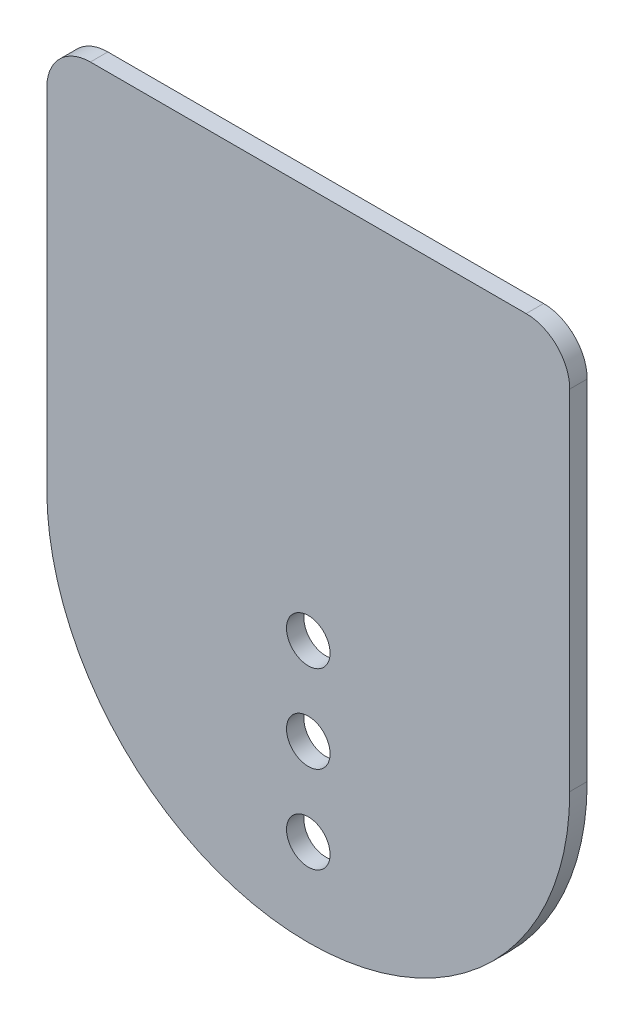
SolidWorks part; units mm, degrees
ref_plane "前视基准面" through (0, 0, 0) normal (0, 0, 1) x (1, 0, 0)
ref_plane "上视基准面" through (0, 0, 0) normal (0, 1, 0) x (1, 0, 0)
ref_plane "右视基准面" through (0, 0, 0) normal (1, 0, 0) x (0, 0, -1)
sketch "草图1" plane through (0, 0, 0) normal (0, 0, 1) x (1, 0, 0)
  line L0 (60, 52.2477) -> (60, -206.2786) construction
  line L1 (10, 0) -> (110, 0)
  line L2 (0, -10) -> (0, -90)
  line L4 (120, -10) -> (120, -90)
  line L5 (60, -130) -> (60, -110) construction
  arc A0 (0, -10) -> (10, 0) centre (10, -10) cw
  arc A1 (120, -10) -> (110, 0) centre (110, -10) ccw
  arc A2 (60, -150) -> (120, -90) centre (60, -90) ccw
  arc A3 (60, -150) -> (0, -90) centre (60, -90) cw
  circle A4 centre (60, -130) radius 5
  circle A5 centre (60, -110) radius 5
  circle A6 centre (60, -90) radius 5
  point P7 (0, 0)
  point P12 (0, 0)
  point P16 (60, 0)
  dimension "D1" = 120
  dimension "D2" = 10
  dimension "D3" = 60
  dimension "D5" = 10
  dimension "D4" = 150
  dimension "D7" = 20
  dimension "D6" = 3
extrude "凸台-拉伸1" add sketch "草图1" along normal mid plane 4
